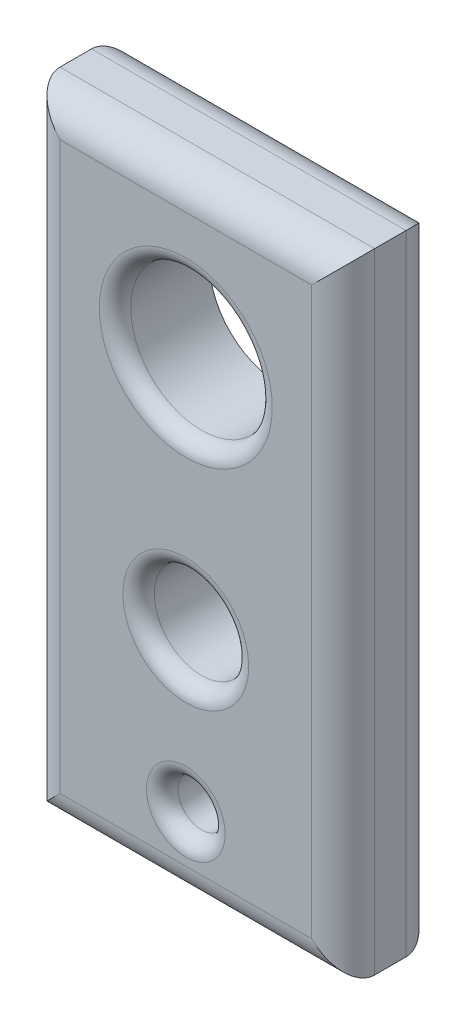
SolidWorks part; units mm, degrees
ref_plane "Front Plane" through (0, 0, 0) normal (0, 0, 1) x (1, 0, 0)
ref_plane "Top Plane" through (0, 0, 0) normal (0, 1, 0) x (1, 0, 0)
ref_plane "Right Plane" through (0, 0, 0) normal (1, 0, 0) x (0, 0, -1)
sketch "Sketch1" plane through (0, 0, 0) normal (0, 0, 1) x (1, 0, 0)
  line L1 (0, 0) -> (2540, 0)
  line L2 (0, 0) -> (0, 5080)
  line L3 (0, 5080) -> (2540, 5080)
  line L4 (2540, 0) -> (2540, 5080)
  dimension "D1" = 2540
  dimension "D2" = 5080
extrude "Boss-Extrude1" add sketch "Sketch1" along normal blind 762
fillet "Fillet1" radius 254 8 edges at (1270, 0, 0) (2540, 2540, 0) (1270, 5080, 0) (0, 2540, 0) (0, 2540, 762) (1270, 0, 762) (2540, 2540, 762) (1270, 5080, 762)
sketch "Sketch2" plane through (0, 0, 762) normal (0, 0, 1) x (1, 0, 0)
  line L0 (2540, 0) -> (0, 0) construction
  line L1 (1270, 4826) -> (1270, 0) construction
  line L2 (2286, 4826) -> (254, 4826) construction
  circle A0 centre (1270, 635) radius 190.5
  circle A1 centre (1270, 1905) radius 381
  circle A2 centre (1270, 3810) radius 571.5
  point P8 (0, 0)
  point P13 (0, 0)
  point P14 (0, 0)
  point P15 (0, 0)
  dimension "D2" = 381
  dimension "D4" = 762
  dimension "D6" = 1143
  dimension "D1" = 635
  dimension "D3" = 1905
  dimension "D5" = 1905
extrude "Cut-Extrude1" cut sketch "Sketch2" against normal through all
fillet "Fillet2" radius 127 3 edges at (1460.5, 635, 762) (1651, 1905, 762) (1841.5, 3810, 762)
